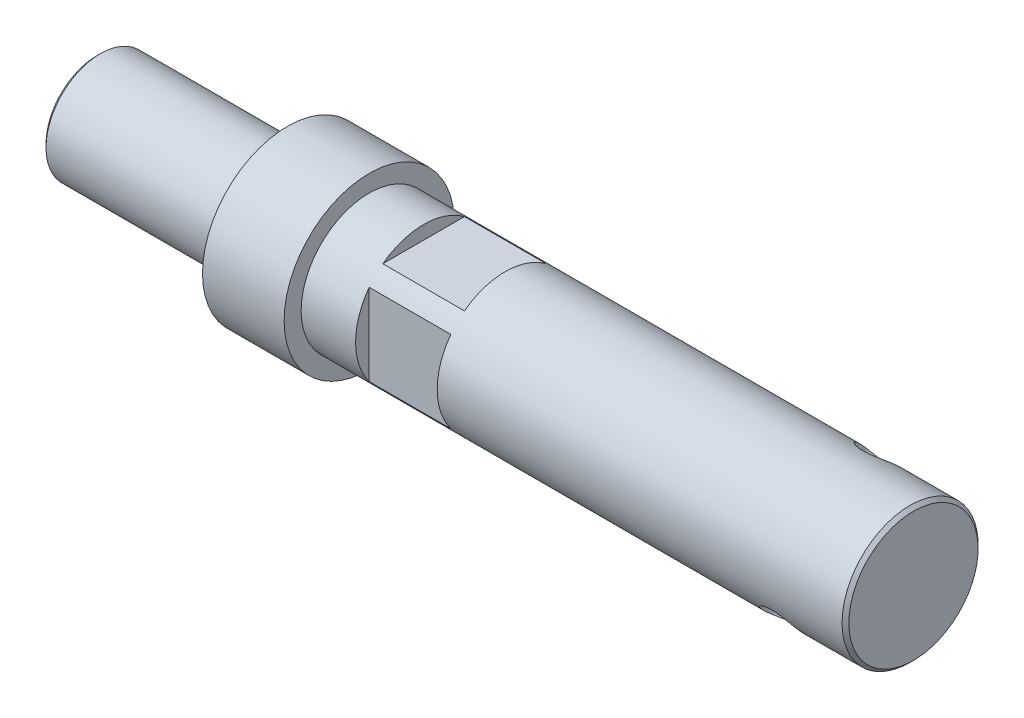
SolidWorks part; units mm, degrees
material "Простая углеродистая сталь"
ref_plane "Спереди" through (0, 0, 0) normal (0, 0, 1) x (1, 0, 0)
ref_plane "Сверху" through (0, 0, 0) normal (0, 1, 0) x (1, 0, 0)
ref_plane "Справа" through (0, 0, 0) normal (1, 0, 0) x (0, 0, -1)
sketch "Эскиз1" plane through (0, 0, 0) normal (0, 0, 1) x (1, 0, 0)
  line L0 (-178.3226, 0) -> (65.8065, 0) construction
  line L1 (0, 0) -> (0, 19)
  line L2 (-1, 20) -> (-160, 20)
  line L3 (-160, 20) -> (-160, 25)
  line L4 (-160, 25) -> (-184, 25)
  line L5 (-184, 25) -> (-184, 16)
  line L6 (-184, 16) -> (-239, 16)
  line L7 (-240, 15) -> (-240, 0)
  line L8 (-240, 0) -> (0, 0)
  line L9 (0, 19) -> (-1, 20)
  line L10 (-239, 16) -> (-240, 15)
  point P4 (0, 20)
  point P10 (-240, 16)
  dimension "D1" = 40
  dimension "D2" = 32
  dimension "D3" = 50
  dimension "D4" = 240
  dimension "D5" = 160
  dimension "D6" = 24
  dimension "D7" = 1
  dimension "D8" = 45
  dimension "D9" = 1
  dimension "D10" = 45
revolve "Повернуть1" add sketch "Эскиз1" angle 360 about L0
ref_plane "Плоскость1" through (-144, 0, 0) normal (1, 0, 0) x (0, 0, -1)
sketch "Эскиз2" plane through (-144, 0, 0) normal (1, 0, 0) x (0, 0, -1)
  line L1 (16, -16) -> (-16, -16)
  line L2 (16, -16) -> (16, 16)
  line L3 (16, 16) -> (-16, 16)
  line L4 (-16, -16) -> (-16, 16)
  line L5 (0, 16) -> (0, -16) construction
  line L6 (16, 0) -> (-16, 0) construction
  point P0 (0, 0)
  dimension "D1" = 32
extrude "Вырез-Вытянуть1" cut sketch "Эскиз2" along normal blind 24 flip side to cut
ref_plane "Плоскость2" through (0, -16, 0) normal (0, -1, 0) x (-1, 0, 0)
sketch "Эскиз3" plane through (0, -16, 0) normal (0, -1, 0) x (-1, 0, 0)
  line L0 (227, 0) -> (197, 0) construction
  line L1 (227, -6) -> (197, -6)
  line L2 (227, 6) -> (197, 6)
  line L3 (239, -16) -> (239, 16) construction
  arc A0 (227, -6) -> (227, 6) centre (227, 0) ccw
  arc A1 (197, 6) -> (197, -6) centre (197, 0) ccw
  point P3 (212, 0)
  dimension "D1" = 12
  dimension "D2" = 30
  dimension "D3" = 12
extrude "Вырез-Вытянуть2" cut sketch "Эскиз3" against normal blind 5
ref_plane "Плоскость3" through (0, 0, 0) normal (0, -0.7071, 0.7071) x (-1, 0, 0)
sketch "Эскиз4" plane through (0, 0, 0) normal (0, -0.7071, 0.7071) x (-1, 0, 0)
  line L0 (1, 0) -> (160, 0) construction
  circle A0 centre (24, 0) radius 6
  point P4 (0, 0)
  dimension "D1" = 12
  dimension "D2" = 24
extrude "Вырез-Вытянуть3" cut sketch "Эскиз4" against normal through all both and the other way through all
